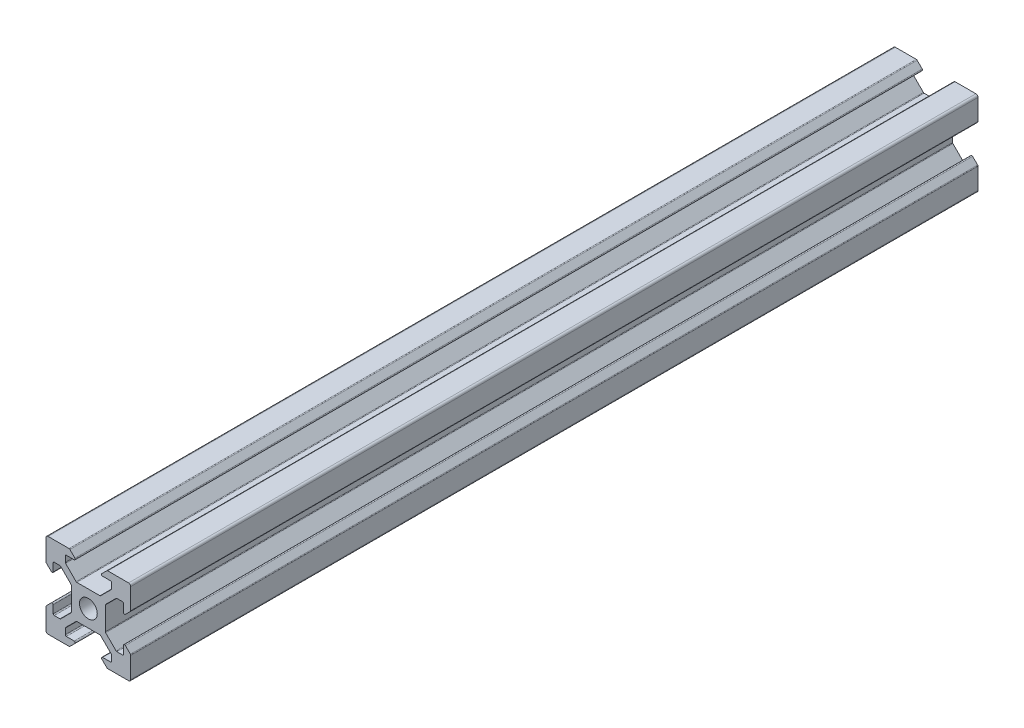
SolidWorks part; units mm, degrees
material "1060 Alloy"
ref_plane "Front Plane" through (0, 0, 0) normal (0, 0, 1) x (1, 0, 0)
ref_plane "Top Plane" through (0, 0, 0) normal (0, 1, 0) x (1, 0, 0)
ref_plane "Right Plane" through (0, 0, 0) normal (1, 0, 0) x (0, 0, -1)
sketch "Model" plane through (0, 0, 0) normal (0, 0, 1) x (1, 0, 0)
  line L0 (2012.9312, 1381.8004) -> (2012.9312, 1378.2004)
  line L1 (2016.4702, 1376.0004) -> (2017.3922, 1376.0004)
  line L2 (2020.9312, 1380.4614) -> (2020.9312, 1379.5394)
  line L3 (2016.4702, 1384.0004) -> (2017.3922, 1384.0004)
  line L270 (2012.9312, 1381.8004) -> (2012.9312, 1382.7004)
  line L271 (2012.8433, 1382.9125) -> (2010.3787, 1385.3772)
  line L272 (2010.2019, 1385.4504) -> (2008.8812, 1385.4504)
  line L273 (2008.6312, 1385.2004) -> (2008.6312, 1383.3504)
  line L274 (2008.2044, 1383.1736) -> (2007.0191, 1384.359)
  line L275 (2006.9312, 1384.5711) -> (2006.9312, 1389.5004)
  line L276 (2007.4312, 1390.0004) -> (2012.3605, 1390.0004)
  line L277 (2012.5726, 1389.9125) -> (2013.758, 1388.7272)
  line L278 (2013.5812, 1388.3004) -> (2011.7312, 1388.3004)
  line L279 (2011.4812, 1388.0504) -> (2011.4812, 1386.7297)
  line L280 (2011.5544, 1386.5529) -> (2014.0338, 1384.0736)
  line L281 (2014.2105, 1384.0004) -> (2016.4702, 1384.0004)
  line L282 (2017.3922, 1384.0004) -> (2019.6519, 1384.0004)
  line L283 (2019.8287, 1384.0736) -> (2022.308, 1386.5529)
  line L284 (2022.3812, 1386.7297) -> (2022.3812, 1388.0504)
  line L285 (2022.1312, 1388.3004) -> (2020.2812, 1388.3004)
  line L286 (2020.1044, 1388.7272) -> (2021.2898, 1389.9125)
  line L287 (2021.5019, 1390.0004) -> (2026.4312, 1390.0004)
  line L288 (2026.9312, 1389.5004) -> (2026.9312, 1384.5711)
  line L289 (2026.8433, 1384.359) -> (2025.658, 1383.1736)
  line L290 (2025.2312, 1383.3504) -> (2025.2312, 1385.2004)
  line L291 (2024.9812, 1385.4504) -> (2023.6605, 1385.4504)
  line L292 (2023.4838, 1385.3772) -> (2021.0044, 1382.8978)
  line L293 (2020.9312, 1382.7211) -> (2020.9312, 1380.4614)
  line L294 (2020.9312, 1379.5394) -> (2020.9312, 1377.2797)
  line L295 (2021.0044, 1377.1029) -> (2023.4838, 1374.6236)
  line L296 (2023.6605, 1374.5504) -> (2024.9812, 1374.5504)
  line L297 (2025.2312, 1374.8004) -> (2025.2312, 1376.6504)
  line L298 (2025.658, 1376.8272) -> (2026.8433, 1375.6418)
  line L299 (2026.9312, 1375.4297) -> (2026.9312, 1370.5004)
  line L300 (2026.4312, 1370.0004) -> (2021.5019, 1370.0004)
  line L301 (2021.2898, 1370.0883) -> (2020.1044, 1371.2736)
  line L302 (2020.2812, 1371.7004) -> (2022.1312, 1371.7004)
  line L303 (2022.3812, 1371.9504) -> (2022.3812, 1373.2711)
  line L304 (2022.308, 1373.4478) -> (2019.8287, 1375.9272)
  line L305 (2019.6519, 1376.0004) -> (2017.3922, 1376.0004)
  line L306 (2016.4702, 1376.0004) -> (2014.2105, 1376.0004)
  line L307 (2014.0338, 1375.9272) -> (2011.5544, 1373.4478)
  line L308 (2011.4812, 1373.2711) -> (2011.4812, 1371.9504)
  line L309 (2011.7312, 1371.7004) -> (2013.5812, 1371.7004)
  line L310 (2013.758, 1371.2736) -> (2012.5726, 1370.0883)
  line L311 (2012.3605, 1370.0004) -> (2007.4312, 1370.0004)
  line L312 (2006.9312, 1370.5004) -> (2006.9312, 1375.4297)
  line L313 (2007.0191, 1375.6418) -> (2008.2044, 1376.8272)
  line L314 (2008.6312, 1376.6504) -> (2008.6312, 1374.8004)
  line L315 (2008.8812, 1374.5504) -> (2010.2019, 1374.5504)
  line L316 (2010.3787, 1374.6236) -> (2012.8433, 1377.0883)
  line L317 (2012.9312, 1377.3004) -> (2012.9312, 1378.2004)
  circle A0 centre (2016.9312, 1380.0004) radius 2.1
  arc A427 (2012.9312, 1382.7004) -> (2012.8433, 1382.9125) centre (2012.6312, 1382.7004) ccw
  arc A428 (2010.3787, 1385.3772) -> (2010.2019, 1385.4504) centre (2010.2019, 1385.2004) ccw
  arc A429 (2008.8812, 1385.4504) -> (2008.6312, 1385.2004) centre (2008.8812, 1385.2004) ccw
  arc A430 (2008.2044, 1383.1736) -> (2008.6312, 1383.3504) centre (2008.3812, 1383.3504) ccw
  arc A431 (2006.9312, 1384.5711) -> (2007.0191, 1384.359) centre (2007.2312, 1384.5711) ccw
  arc A432 (2007.4312, 1390.0004) -> (2006.9312, 1389.5004) centre (2007.4312, 1389.5004) ccw
  arc A433 (2012.5726, 1389.9125) -> (2012.3605, 1390.0004) centre (2012.3605, 1389.7004) ccw
  arc A434 (2013.5812, 1388.3004) -> (2013.758, 1388.7272) centre (2013.5812, 1388.5504) ccw
  arc A435 (2011.7312, 1388.3004) -> (2011.4812, 1388.0504) centre (2011.7312, 1388.0504) ccw
  arc A436 (2011.4812, 1386.7297) -> (2011.5544, 1386.5529) centre (2011.7312, 1386.7297) ccw
  arc A437 (2014.0338, 1384.0736) -> (2014.2105, 1384.0004) centre (2014.2105, 1384.2504) ccw
  arc A441 (2019.6519, 1384.0004) -> (2019.8287, 1384.0736) centre (2019.6519, 1384.2504) ccw
  arc A442 (2022.308, 1386.5529) -> (2022.3812, 1386.7297) centre (2022.1312, 1386.7297) ccw
  arc A443 (2022.3812, 1388.0504) -> (2022.1312, 1388.3004) centre (2022.1312, 1388.0504) ccw
  arc A444 (2020.1044, 1388.7272) -> (2020.2812, 1388.3004) centre (2020.2812, 1388.5504) ccw
  arc A445 (2021.5019, 1390.0004) -> (2021.2898, 1389.9125) centre (2021.5019, 1389.7004) ccw
  arc A446 (2026.9312, 1389.5004) -> (2026.4312, 1390.0004) centre (2026.4312, 1389.5004) ccw
  arc A447 (2026.8433, 1384.359) -> (2026.9312, 1384.5711) centre (2026.6312, 1384.5711) ccw
  arc A448 (2025.2312, 1383.3504) -> (2025.658, 1383.1736) centre (2025.4812, 1383.3504) ccw
  arc A449 (2025.2312, 1385.2004) -> (2024.9812, 1385.4504) centre (2024.9812, 1385.2004) ccw
  arc A450 (2023.6605, 1385.4504) -> (2023.4838, 1385.3772) centre (2023.6605, 1385.2004) ccw
  arc A451 (2021.0044, 1382.8978) -> (2020.9312, 1382.7211) centre (2021.1812, 1382.7211) ccw
  arc A455 (2020.9312, 1377.2797) -> (2021.0044, 1377.1029) centre (2021.1812, 1377.2797) ccw
  arc A456 (2023.4838, 1374.6236) -> (2023.6605, 1374.5504) centre (2023.6605, 1374.8004) ccw
  arc A457 (2024.9812, 1374.5504) -> (2025.2312, 1374.8004) centre (2024.9812, 1374.8004) ccw
  arc A458 (2025.658, 1376.8272) -> (2025.2312, 1376.6504) centre (2025.4812, 1376.6504) ccw
  arc A459 (2026.9312, 1375.4297) -> (2026.8433, 1375.6418) centre (2026.6312, 1375.4297) ccw
  arc A460 (2026.4312, 1370.0004) -> (2026.9312, 1370.5004) centre (2026.4312, 1370.5004) ccw
  arc A461 (2021.2898, 1370.0883) -> (2021.5019, 1370.0004) centre (2021.5019, 1370.3004) ccw
  arc A462 (2020.2812, 1371.7004) -> (2020.1044, 1371.2736) centre (2020.2812, 1371.4504) ccw
  arc A463 (2022.1312, 1371.7004) -> (2022.3812, 1371.9504) centre (2022.1312, 1371.9504) ccw
  arc A464 (2022.3812, 1373.2711) -> (2022.308, 1373.4478) centre (2022.1312, 1373.2711) ccw
  arc A465 (2019.8287, 1375.9272) -> (2019.6519, 1376.0004) centre (2019.6519, 1375.7504) ccw
  arc A469 (2014.2105, 1376.0004) -> (2014.0338, 1375.9272) centre (2014.2105, 1375.7504) ccw
  arc A470 (2011.5544, 1373.4478) -> (2011.4812, 1373.2711) centre (2011.7312, 1373.2711) ccw
  arc A471 (2011.4812, 1371.9504) -> (2011.7312, 1371.7004) centre (2011.7312, 1371.9504) ccw
  arc A472 (2013.758, 1371.2736) -> (2013.5812, 1371.7004) centre (2013.5812, 1371.4504) ccw
  arc A473 (2012.3605, 1370.0004) -> (2012.5726, 1370.0883) centre (2012.3605, 1370.3004) ccw
  arc A474 (2006.9312, 1370.5004) -> (2007.4312, 1370.0004) centre (2007.4312, 1370.5004) ccw
  arc A475 (2007.0191, 1375.6418) -> (2006.9312, 1375.4297) centre (2007.2312, 1375.4297) ccw
  arc A476 (2008.6312, 1376.6504) -> (2008.2044, 1376.8272) centre (2008.3812, 1376.6504) ccw
  arc A477 (2008.6312, 1374.8004) -> (2008.8812, 1374.5504) centre (2008.8812, 1374.8004) ccw
  arc A478 (2010.2019, 1374.5504) -> (2010.3787, 1374.6236) centre (2010.2019, 1374.8004) ccw
  arc A479 (2012.8433, 1377.0883) -> (2012.9312, 1377.3004) centre (2012.6312, 1377.3004) ccw
extrude "Boss-Extrude1" add sketch "Model" along normal blind 200
